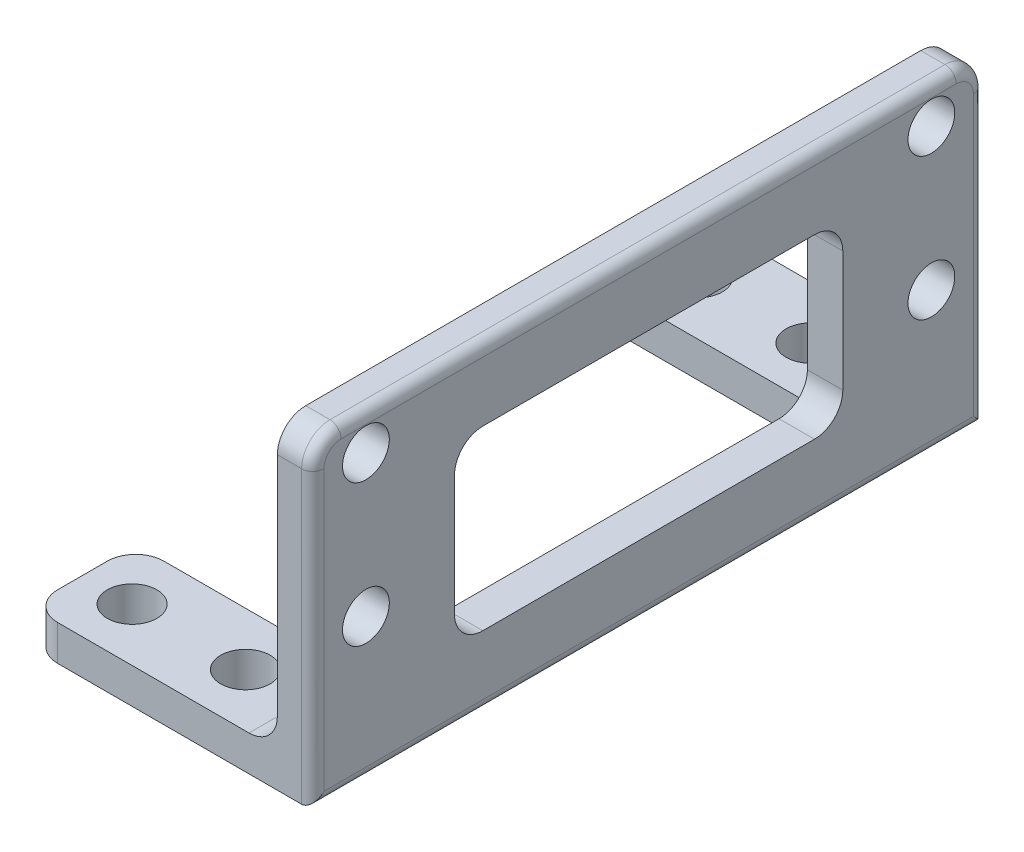
SolidWorks part; units mm, degrees
ref_plane "Front Plane" through (0, 0, 0) normal (0, 0, 1) x (1, 0, 0)
ref_plane "Top Plane" through (0, 0, 0) normal (0, 1, 0) x (1, 0, 0)
ref_plane "Right Plane" through (0, 0, 0) normal (1, 0, 0) x (0, 0, -1)
sketch "Sketch1" plane through (0, 0, 0) normal (0, 1, 0) x (1, 0, 0)
  line L0 (0, -4.7625) -> (0, -50.673) construction
  line L1 (-12.7, -4.7625) -> (12.7, -4.7625) construction
  line L2 (-12.7, -4.7625) -> (-12.7, 4.7625)
  line L3 (-12.7, 4.7625) -> (12.7, 4.7625)
  line L4 (12.7, -4.7625) -> (12.7, 4.7625)
  line L5 (-12.7, -4.7625) -> (12.7, 4.7625) construction
  line L6 (-12.7, 4.7625) -> (12.7, -4.7625) construction
  line L7 (-12.7, -4.7625) -> (9.525, -4.7625)
  line L8 (-12.7, -55.4355) -> (12.7, -55.4355)
  line L9 (-12.7, -55.4355) -> (-12.7, -45.9105)
  line L10 (-12.7, -45.9105) -> (12.7, -45.9105) construction
  line L11 (12.7, -55.4355) -> (12.7, -45.9105)
  line L12 (-12.7, -55.4355) -> (12.7, -45.9105) construction
  line L13 (-12.7, -45.9105) -> (12.7, -55.4355) construction
  line L14 (9.525, -4.7625) -> (9.525, -45.9105)
  line L15 (9.525, -45.9105) -> (-12.7, -45.9105)
  line L17 (12.7, -45.9105) -> (12.7, -4.7625)
  point P0 (0, 0)
  point P8 (0, -50.673)
  dimension "D1" = 25.4
  dimension "D2" = 9.525
  dimension "D3" = 41.148
  dimension "D4" = 3.175
extrude "Boss-Extrude1" add sketch "Sketch1" along normal blind 3.175
sketch "Sketch2" plane through (0, 3.175, 0) normal (0, 1, 0) x (1, 0, 0)
  line L0 (-12.7, 0) -> (12.7, 0) construction
  line L1 (-12.7, 4.7625) -> (-12.7, -4.7625) construction
  line L3 (12.7, -55.4355) -> (12.7, 4.7625) construction
  line L4 (-12.7, -50.673) -> (12.7, -50.673) construction
  line L6 (-12.7, -45.9105) -> (-12.7, -55.4355) construction
  circle A0 centre (-8.255, 0) radius 2.2225
  circle A1 centre (1.905, 0) radius 2.2225
  circle A2 centre (-8.255, -50.673) radius 2.2225
  circle A3 centre (1.905, -50.673) radius 2.2225
  dimension "D1" = 4.445
  dimension "D3" = 4.445
  dimension "D4" = 10.16
extrude "Cut-Extrude1" cut sketch "Sketch2" against normal through all
sketch "Sketch5" plane through (0, 3.175, 0) normal (0, 1, 0) x (1, 0, 0)
  line L0 (12.7, 4.7625) -> (12.7, -55.4355)
  line L1 (12.7, -55.4355) -> (9.525, -55.4355)
  line L2 (-12.7, -55.4355) -> (12.7, -55.4355) construction
  line L3 (9.525, -55.4355) -> (9.525, 4.7625)
  line L4 (12.7, 4.7625) -> (-12.7, 4.7625) construction
  line L5 (9.525, 4.7625) -> (12.7, 4.7625)
  line L7 (9.525, -4.7625) -> (9.525, -45.9105) construction
extrude "Boss-Extrude3" add sketch "Sketch5" along normal blind 25.4
sketch "Sketch6" plane through (9.525, 0, 0) normal (-1, 0, 0) x (0, 0, 1)
  line L0 (50.673, 3.175) -> (50.673, 28.575) construction
  line L1 (45.9105, 3.175) -> (55.4355, 3.175) construction
  line L2 (-4.7625, 28.575) -> (55.4355, 28.575) construction
  line L3 (0, 3.175) -> (0, 28.575) construction
  line L4 (-4.7625, 3.175) -> (4.7625, 3.175) construction
  line L5 (0, 25.4) -> (50.673, 25.4) construction
  line L6 (0, 12.7) -> (50.673, 12.7) construction
  circle A0 centre (0, 25.4) radius 2.0955
  circle A1 centre (0, 12.7) radius 2.0955
  circle A2 centre (50.673, 25.4) radius 2.0955
  circle A3 centre (50.673, 12.7) radius 2.0955
  dimension "D3" = 4.191
  dimension "D1" = 3.175
  dimension "D2" = 12.7
extrude "Cut-Extrude3" cut sketch "Sketch6" against normal through all
sketch "Sketch8" plane through (9.525, 0, 0) normal (-1, 0, 0) x (0, 0, 1)
  line L0 (25.3365, 28.575) -> (25.3365, 0) construction
  line L1 (-4.7625, 28.575) -> (55.4355, 28.575) construction
  line L2 (4.7625, 0) -> (45.9105, 0) construction
  line L3 (55.4355, 28.575) -> (55.4355, 3.175) construction
  line L4 (7.9375, 6.35) -> (42.7355, 6.35)
  line L5 (7.9375, 6.35) -> (7.9375, 22.225)
  line L6 (7.9375, 22.225) -> (42.7355, 22.225)
  line L7 (42.7355, 6.35) -> (42.7355, 22.225)
  line L8 (7.9375, 6.35) -> (42.7355, 22.225) construction
  line L9 (7.9375, 22.225) -> (42.7355, 6.35) construction
  point P6 (25.3365, 14.2875)
  dimension "D1" = 6.35
  dimension "D2" = 12.7
extrude "Cut-Extrude4" cut sketch "Sketch8" against normal through all
fillet "Fillet1" radius 2.54 14 edges at (-12.7, 1.5875, 4.7625) (-12.7, 1.5875, -4.7625) (11.1125, 28.575, -4.7625) (11.1125, 28.575, 55.4355) (-12.7, 1.5875, 55.4355) (-12.7, 1.5875, 45.9105) (11.1125, 6.35, 42.7355) (11.1125, 22.225, 42.7355) (11.1125, 22.225, 7.9375) (11.1125, 6.35, 7.9375)
fillet "Fillet2" radius 1 6 edges at (12.7, 13.0175, 55.4355) (12.7, 27.8311, 54.6916) (12.7, 28.575, 25.3365) (12.7, 27.8311, -4.0186) (12.7, 13.0175, -4.7625) (12.7, 0, 25.3365)
